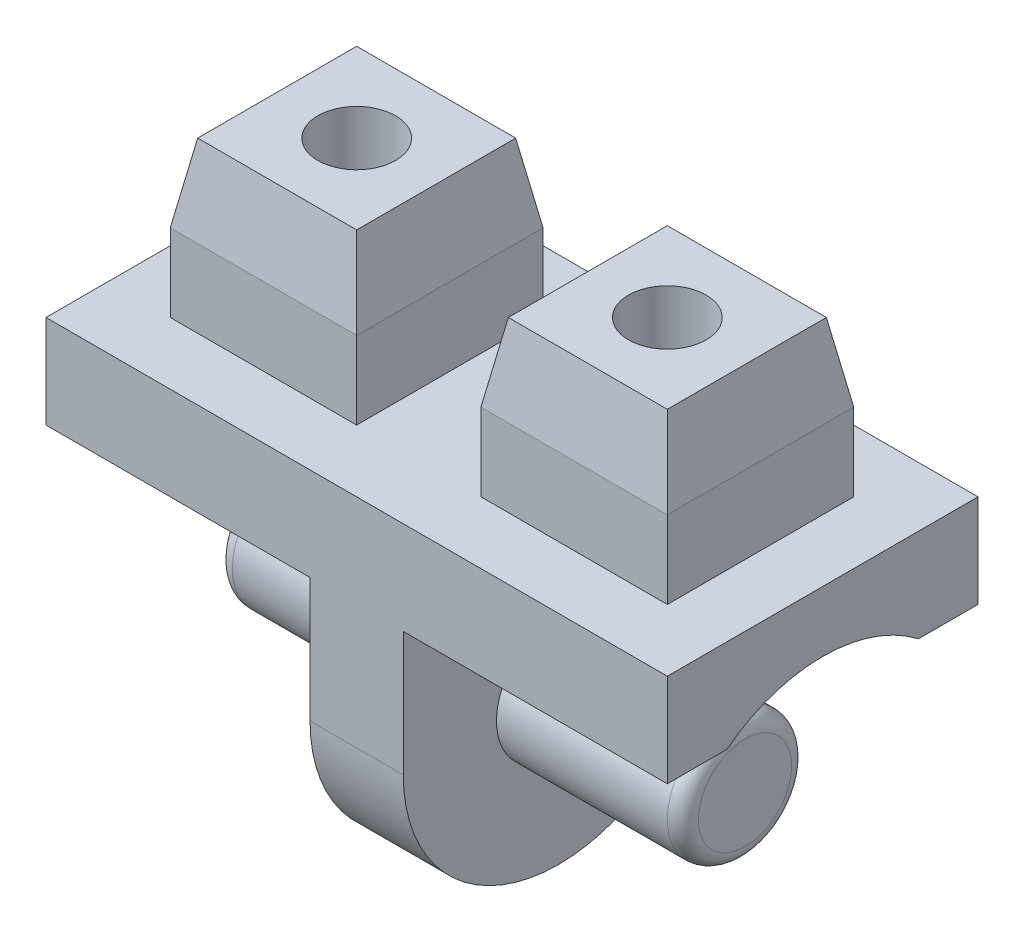
SolidWorks part; units mm, degrees
material "ABS"
ref_plane "Front Plane" through (0, 0, 0) normal (0, 0, 1) x (1, 0, 0)
ref_plane "Top Plane" through (0, 0, 0) normal (0, 1, 0) x (1, 0, 0)
ref_plane "Right Plane" through (0, 0, 0) normal (1, 0, 0) x (0, 0, -1)
sketch "Sketch1" plane through (0, 0, 0) normal (1, 0, 0) x (0, 0, -1)
  line L0 (-5, 0) -> (5, 0)
  line L1 (5, 0) -> (5, -7)
  line L2 (-5, 0) -> (-5, -7)
  arc A0 (-5, -7) -> (5, -7) centre (0, -7) ccw
  arc A1 (-5, -7) -> (5, -7) centre (0, -7) cw construction
  point P7 (0, 0)
  dimension "D1" = 10
  dimension "D2" = 7
extrude "Leg connector" add sketch "Sketch1" along normal blind 1.5
sketch "Sketch2" plane through (1.5, 0, 0) normal (1, 0, 0) x (0, 0, -1)
  line L0 (-5, 0) -> (5, 0)
  line L1 (5, 0) -> (5, -3)
  line L2 (5, -7) -> (5, 0) construction
  line L3 (5, -3) -> (3.0826, -3)
  line L4 (-5, 0) -> (-5, -3)
  line L5 (-5, 0) -> (-5, -7) construction
  line L6 (-5, -3) -> (-3.0826, -3)
  line L7 (-5, -7) -> (5, -7) construction
  arc A0 (-5, -7) -> (5, -7) centre (0, -7) cw construction
  arc A1 (-3.0826, -3) -> (3.0826, -3) centre (0, -7) cw
  circle A2 centre (0, -7) radius 5.05 construction
  point P17 (0, -7)
  dimension "D2" = 10.1
  dimension "D1" = 3
extrude "Torso connector" add sketch "Sketch2" along normal blind 8.5
sketch "Sketch3" plane through (1.5, 0, 0) normal (1, 0, 0) x (0, 0, -1)
  line L0 (-5, -7) -> (5, -7) construction
  circle A0 centre (0, -7) radius 2
  dimension "D1" = 4
extrude "Leg pin" add sketch "Sketch3" along normal blind 6
sketch "Sketch4" plane through (0, 0, 0) normal (0, 1, 0) x (1, 0, 0)
  line L0 (10, -5) -> (0, -5) construction
  line L1 (2, -3) -> (8, -3)
  line L2 (2, -3) -> (2, 3)
  line L3 (2, 3) -> (8, 3)
  line L4 (8, -3) -> (8, 3)
  point P4 (2, 0)
  point P6 (5, -3)
  point P9 (5, -5)
  dimension "D1" = 6
  dimension "D2" = 6
extrude "Torso pin base" add sketch "Sketch4" along normal blind 2.5
sketch "Sketch5" plane through (0, 2.5, 0) normal (0, 1, 0) x (1, 0, 0)
  line L1 (2, -3) -> (8, -3)
  line L2 (2, -3) -> (2, 3)
  line L3 (2, 3) -> (8, 3)
  line L4 (8, -3) -> (8, 3)
extrude "Torso pin tip" add sketch "Sketch5" along normal blind 2.5 draft 10
hole_wizard "Hole that make it easy to add center lines" positions "Sketch8" profile "Sketch7" hole size "Ø2.5" standard "ANSI Metric"
sketch "Sketch8" plane through (0, 5, 0) normal (0, 1, 0) x (1, 0, 0)
  point P0 (5, 0)
sketch "Sketch7" plane through (5, 5, 0) normal (1, 0, 0) x (0, 0, 1)
  line L0 (0, 0) -> (0, 4.2511)
  line L1 (0, 4.2511) -> (1.25, 3.5)
  line L2 (1.25, 3.5) -> (1.25, 0)
  line L5 (1.25, 0) -> (0, 0)
  line L10 (0, 4.2511) -> (-1.25, 3.5) construction
  line L11 (0, -6.35) -> (0, 107.95) construction
  dimension "Hole Dia." = 2.5
  dimension "Hole Depth" = 3.5
  dimension "Drill Angle" = 118
fillet "Smoothing edges" [suppressed] radius 0.1
fillet "Easy leg insert" radius 0.5 1 edges at (7.5, -7, -2)
mirror "Making symetrical" about plane through (0, -7, 0) normal (1, 0, 0) of bodies 109 107
scale "Scale1" scale about centroid uniform scaling yes scale factor 2
